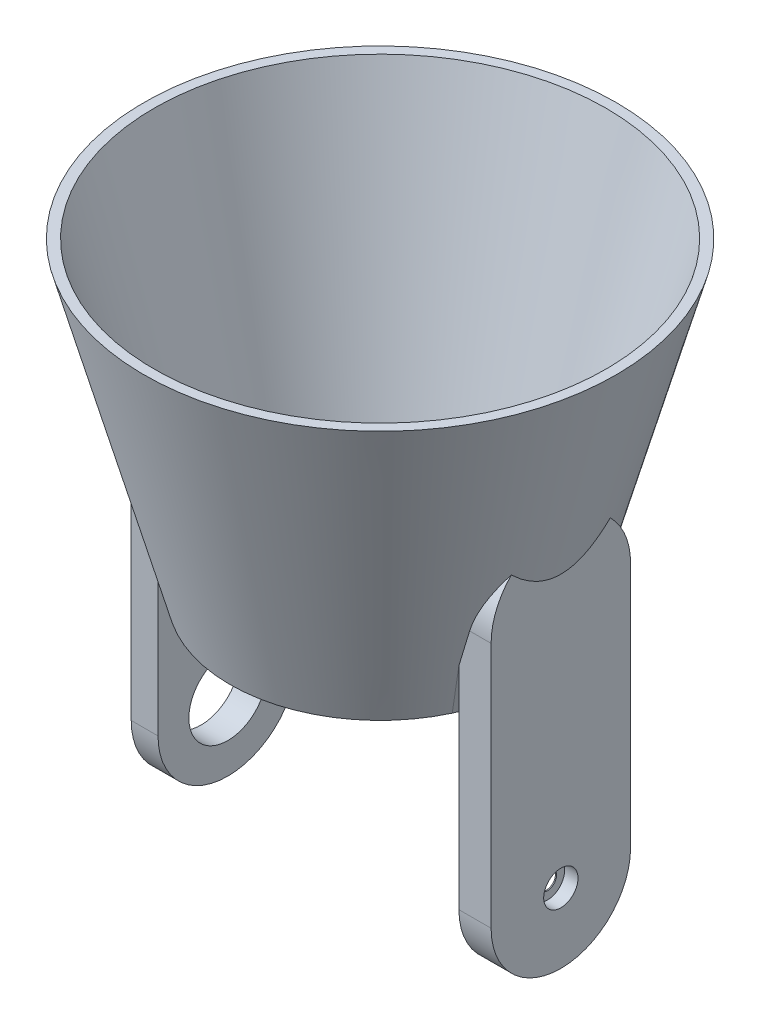
SolidWorks part; units mm, degrees
ref_plane "Front Plane" through (0, 0, 0) normal (0, 0, 1) x (1, 0, 0)
ref_plane "Top Plane" through (0, 0, 0) normal (0, 1, 0) x (1, 0, 0)
ref_plane "Right Plane" through (0, 0, 0) normal (1, 0, 0) x (0, 0, -1)
sketch "Sketch1" plane through (0, 0, 0) normal (0, 0, 1) x (1, 0, 0)
  line L0 (0, 0) -> (0, 100) construction
  line L1 (3.5, 30) -> (28, 30)
  line L2 (28, 30) -> (44, 88)
  line L3 (44, 88) -> (42.1328, 88)
  line L4 (42.1328, 88) -> (26.6845, 32)
  line L5 (26.6845, 32) -> (3.5, 32)
  line L6 (3.5, 32) -> (3.5, 30)
revolve "Cone" add sketch "Sketch1" angle 360 about L0
sketch "Sketch2" plane through (0, 0, 0) normal (1, 0, 0) x (0, 0, -1)
  line L0 (-13, 0) -> (-13, 46)
  line L1 (13, 46) -> (13, 0)
  arc A0 (-13, 46) -> (13, 46) centre (0, 46) cw
  arc A1 (13, 0) -> (-13, 0) centre (0, 0) cw
extrude "Drive arm" add sketch "Sketch2" along normal blind 6 from offset 27.7
sketch "Sketch3" plane through (0, 0, 0) normal (1, 0, 0) x (0, 0, -1)
  line L0 (-13, 0) -> (-13, 46)
  line L1 (13, 46) -> (13, 0)
  arc A0 (-13, 46) -> (13, 46) centre (0, 46) cw
  arc A1 (13, 0) -> (-13, 0) centre (0, 0) cw
extrude "Idler arm" add sketch "Sketch3" along normal blind 5 from offset 33.4
sketch "Sketch4" plane through (0, 0, 0) normal (0, 0, 1) x (1, 0, 0)
  line L0 (0, 0) -> (0, 100) construction
  line L1 (0, 32) -> (26.6845, 32)
  line L2 (26.6845, 32) -> (42.4086, 89)
  line L3 (42.4086, 89) -> (0, 89)
  line L4 (0, 89) -> (0, 32)
revolve "Hollow" cut sketch "Sketch4" angle 360 about L0
sketch "Sketch5" plane through (0, 0, 0) normal (1, 0, 0) x (0, 0, -1)
  line L0 (-4.4, -11.1) -> (-4.4, 11.1)
  line L1 (4.4, 11.1) -> (4.4, -11.1)
  arc A0 (-4.4, 11.1) -> (4.4, 11.1) centre (0, 11.1) cw
  arc A1 (4.4, -11.1) -> (-4.4, -11.1) centre (0, -11.1) cw
extrude "Horn pocket" cut sketch "Sketch5" along normal blind 3.5 from offset 27.5
sketch "Sketch6" plane through (0, 0, 0) normal (1, 0, 0) x (0, 0, -1)
  circle A0 centre (0, 0) radius 7.6
extrude "Hub relief" cut sketch "Sketch6" along normal blind 1.4 from offset 27.5
sketch "Sketch7" plane through (0, 0, 0) normal (1, 0, 0) x (0, 0, -1)
  circle A0 centre (0, 0) radius 1.7
extrude "Hub bolt" cut sketch "Sketch7" along normal blind 6.4 from offset 27.5
sketch "Sketch8" plane through (0, 0, 0) normal (1, 0, 0) x (0, 0, -1)
  circle A0 centre (0, 0) radius 3.2
extrude "Hub counterbore" cut sketch "Sketch8" along normal blind 2.7 from offset 31.2
sketch "Sketch9" plane through (0, 0, 0) normal (1, 0, 0) x (0, 0, -1)
  circle A0 centre (0, 0) radius 7.25
extrude "Idler bore" cut sketch "Sketch9" along normal blind 5.4 from offset 33.6
